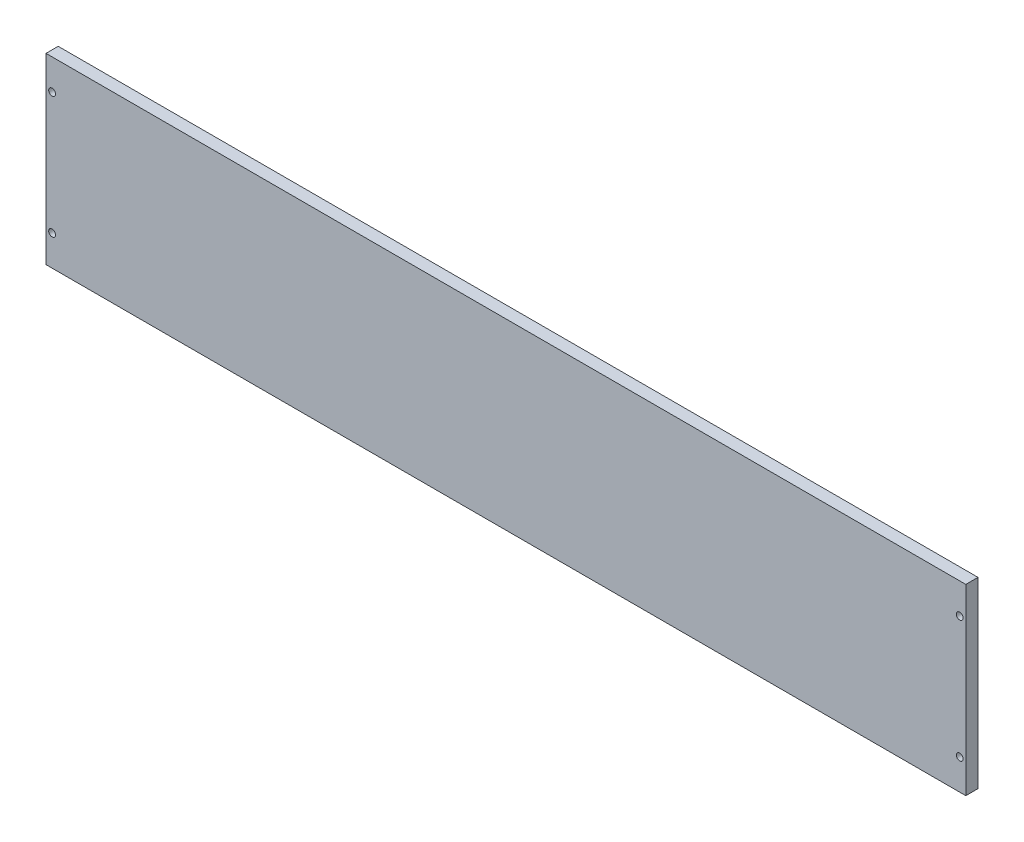
SolidWorks part; units mm, degrees
ref_plane "Front Plane" through (0, 0, 0) normal (0, 0, 1) x (1, 0, 0)
ref_plane "Top Plane" through (0, 0, 0) normal (0, 1, 0) x (1, 0, 0)
ref_plane "Right Plane" through (0, 0, 0) normal (1, 0, 0) x (0, 0, -1)
sketch "Sketch1" plane through (0, 0, 0) normal (0, 0, 1) x (1, 0, 0)
  line L1 (0, 0) -> (383.0066, 0)
  line L2 (0, 0) -> (0, 76.2)
  line L3 (0, 76.2) -> (383.0066, 76.2)
  line L4 (383.0066, 0) -> (383.0066, 76.2)
  dimension "D1" = 383.0066
  dimension "D2" = 76.2
extrude "Boss-Extrude1" add sketch "Sketch1" along normal blind 5.08
sketch "Sketch2" plane through (0, 0, 5.08) normal (0, 0, 1) x (1, 0, 0)
  line L0 (2.54, 76.2) -> (2.54, 0) construction
  line L1 (383.0066, 76.2) -> (0, 76.2) construction
  line L2 (0, 0) -> (383.0066, 0) construction
  line L3 (380.4666, 76.2) -> (380.4666, 0) construction
  line L4 (0, 76.2) -> (0, 0) construction
  line L5 (383.0066, 0) -> (383.0066, 76.2) construction
  circle A0 centre (2.54, 63.5) radius 1.4224
  circle A1 centre (2.54, 12.7) radius 1.4224
  circle A2 centre (380.4666, 63.5) radius 1.4224
  circle A3 centre (380.4666, 12.7) radius 1.4224
  dimension "D3" = 12.7
  dimension "D1" = 2.54
  dimension "D2" = 2.54
  dimension "D4" = 12.7
  dimension "D5" = 12.7
  dimension "D6" = 12.7
extrude "Cut-Extrude1" cut sketch "Sketch2" against normal blind 5.08
